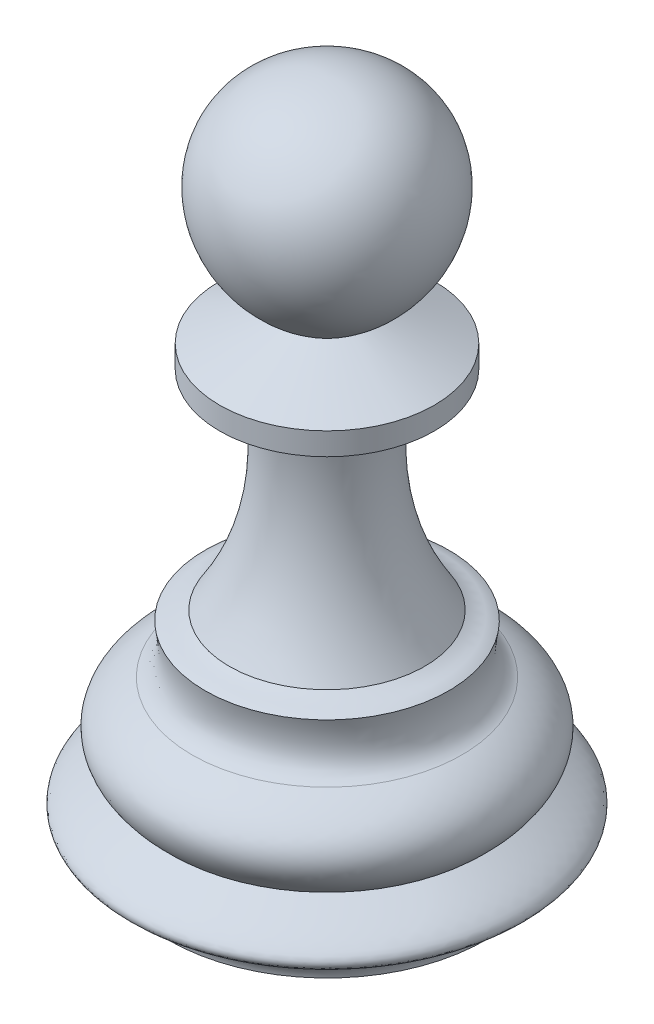
SolidWorks part; units mm, degrees
ref_plane "Front Plane" through (0, 0, 0) normal (0, 0, 1) x (1, 0, 0)
ref_plane "Top Plane" through (0, 0, 0) normal (0, 1, 0) x (1, 0, 0)
ref_plane "Right Plane" through (0, 0, 0) normal (1, 0, 0) x (0, 0, -1)
sketch "Sketch1" plane through (0, 0, 0) normal (0, 0, 1) x (1, 0, 0)
  line L0 (0, 0) -> (120.0423, 0)
  line L2 (0, 506.6276) -> (0, 0)
  line L3 (47.2316, 314.2178) -> (81.2419, 314.2178)
  line L4 (81.2419, 314.2178) -> (81.2419, 331.1814)
  line L5 (81.2419, 331.1814) -> (27.4957, 354.3594)
  spline S0 degree 3 poles (120.0423, 0) (121.1583, 9.5144) (128.3056, 14.2796) (136.6203, 19.3086) knots 0 0 0 0 1 1 1 1
  spline S1 degree 3 poles (136.6203, 19.3086) (160.6022, 28.849) (150.9851, 35.5043) (116.7988, 53.9061) knots 0 0 0 0 1 1 1 1
  spline S2 degree 3 poles (116.7988, 53.9061) (142.2727, 76.5573) (133.5196, 98.1874) (102.0491, 112.3491) knots 0 0 0 0 1 1 1 1
  spline S3 degree 2 poles (102.0491, 112.3491) (85.6747, 120.1394) (92.2257, 149.5101) knots 0 0 0 1 1 1
  spline S4 degree 3 poles (92.2257, 149.5101) (85.2944, 153.0542) (82.666, 151.8787) (73.9723, 156.3799) knots 0 0 0 0 1 1 1 1
  spline S5 degree 2 poles (73.9723, 156.3799) (29.5316, 225.071) (47.2316, 314.2178) knots 0 0 0 1 1 1
  spline S6 degree 3 poles (27.4957, 354.3594) (107.4746, 401.3696) (87.1886, 504.9895) (0, 506.6276) knots 0 0 0 0 1 1 1 1
revolve "Revolve1" add sketch "Sketch1" angle 360 about L2
scale "Scale1" scale about origin uniform scaling yes scale factor 0.5
